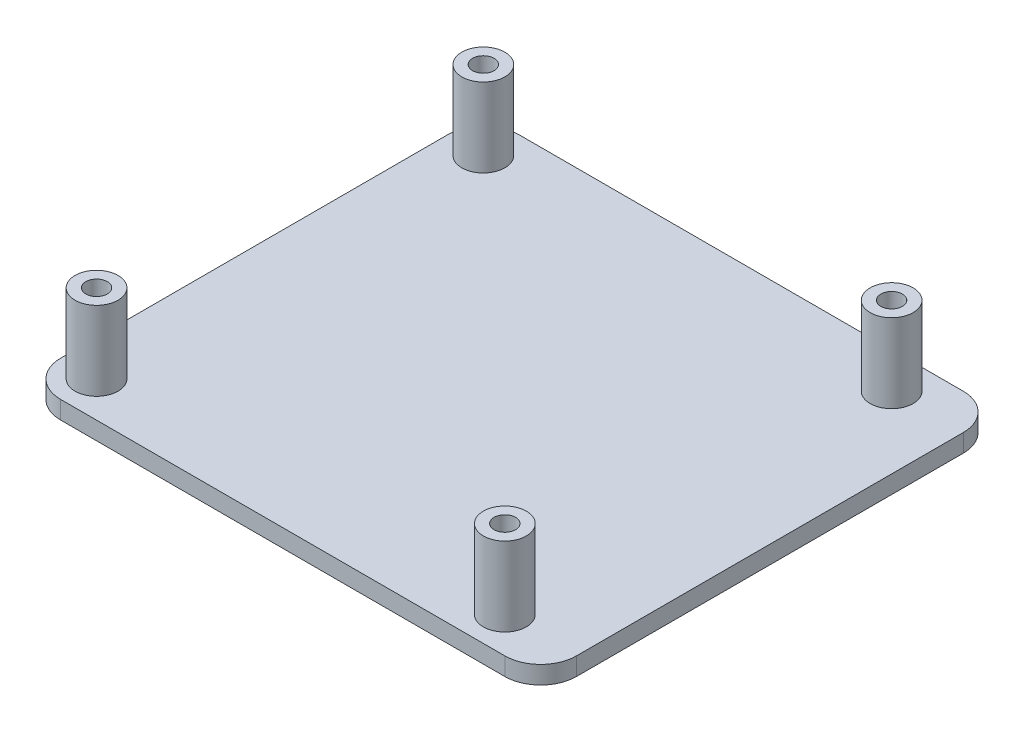
SolidWorks part; units mm, degrees
ref_plane "Front Plane" through (0, 0, 0) normal (0, 0, 1) x (1, 0, 0)
ref_plane "Top Plane" through (0, 0, 0) normal (0, 1, 0) x (1, 0, 0)
ref_plane "Right Plane" through (0, 0, 0) normal (1, 0, 0) x (0, 0, -1)
sketch "Sketch1" plane through (0, 0, 0) normal (0, 1, 0) x (1, 0, 0)
  line L1 (-36, 32) -> (36, 32)
  line L2 (-36, 32) -> (-36, -32)
  line L3 (-36, -32) -> (36, -32)
  line L4 (36, 32) -> (36, -32)
  dimension "D1" = 72
  dimension "D2" = 64
  dimension "D3" = 32
  dimension "D4" = 36
extrude "Boss-Extrude1" add sketch "Sketch1" along normal blind 2.5
sketch "Sketch2" plane through (0, 2.5, 0) normal (0, 1, 0) x (1, 0, 0)
  line L1 (-36, 32) -> (-36, -32) construction
  circle A0 centre (-31, 27) radius 3
  circle A1 centre (26, 27) radius 3
  circle A2 centre (-31, -27) radius 3
  circle A3 centre (26, -27) radius 3
  dimension "D1" = 6
  dimension "D2" = 6
  dimension "D3" = 6
  dimension "D4" = 6
  dimension "D9" = 5
  dimension "D10" = 5
  dimension "D5" = 57
  dimension "D6" = 57
  dimension "D7" = 54
  dimension "D8" = 54
  dimension "D11" = 27
extrude "Boss-Extrude2" add sketch "Sketch2" along normal blind 11
sketch "Sketch3" plane through (0, 13.5, 0) normal (0, 1, 0) x (1, 0, 0)
  circle A0 centre (-31, 27) radius 1.5
  circle A1 centre (-31, -27) radius 1.5
  circle A2 centre (26, 27) radius 1.5
  circle A3 centre (26, -27) radius 1.5
  dimension "D1" = 3
  dimension "D2" = 3
  dimension "D3" = 3
  dimension "D4" = 3
extrude "Cut-Extrude1" cut sketch "Sketch3" against normal through all both and the other way through all
fillet "Fillet1" radius 5 4 edges at (-36, 1.25, 32) (36, 1.25, 32) (36, 1.25, -32) (-36, 1.25, -32)
